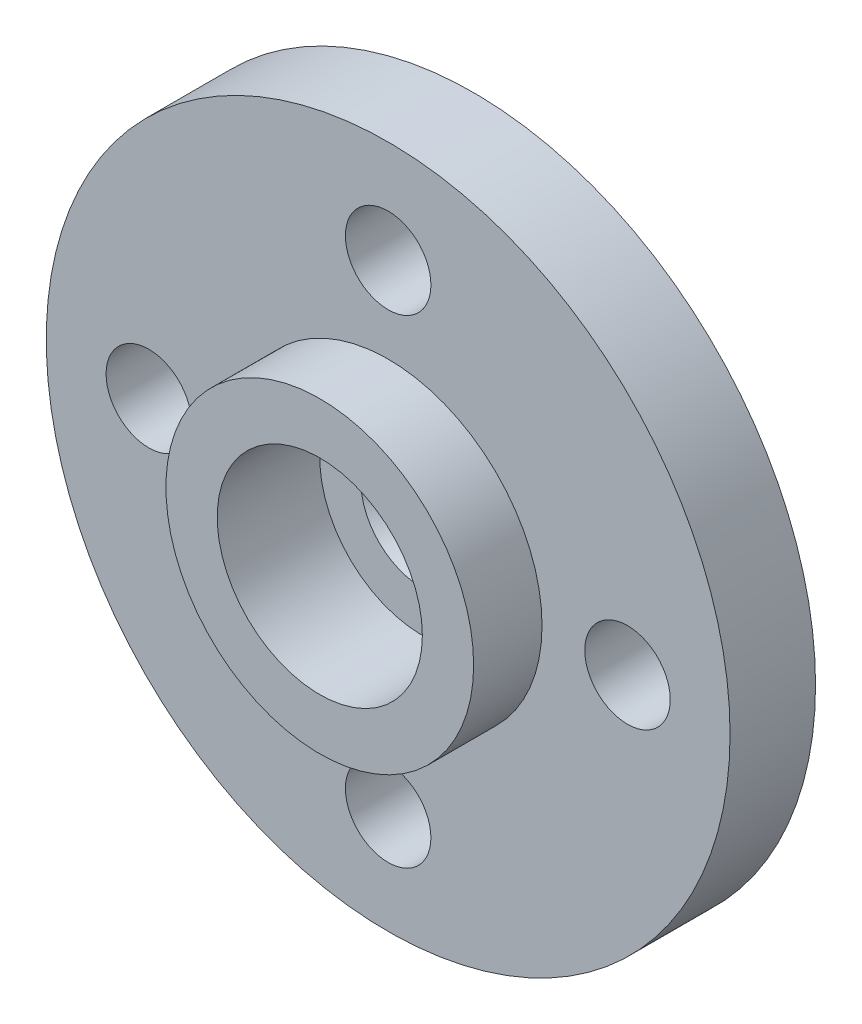
SolidWorks part; units mm, degrees
ref_plane "前视基准面" through (0, 0, 0) normal (0, 0, 1) x (1, 0, 0)
ref_plane "上视基准面" through (0, 0, 0) normal (0, 1, 0) x (1, 0, 0)
ref_plane "右视基准面" through (0, 0, 0) normal (1, 0, 0) x (0, 0, -1)
other "Configuration Table"
sketch "草图1" plane through (0, 0, 0) normal (0, 0, 1) x (1, 0, 0)
  circle A0 centre (0, 0) radius 10
  circle A1 centre (0, 0) radius 7 construction
  circle A2 centre (0, 7) radius 0.5
  circle A3 centre (7, 0) radius 0.5
  circle A4 centre (0, -7) radius 0.5
  circle A5 centre (-7, 0) radius 0.5
  circle A6 centre (0, 0) radius 1.5
  dimension "D1" = 1
  dimension "D2" = 1
  dimension "D3" = 1
  dimension "D4" = 1
  dimension "D5" = 20
  dimension "D6" = 14
  dimension "D7" = 3
extrude "凸台-拉伸1" add sketch "草图1" along normal blind 2.5
sketch "草图2" plane through (0, 0, 2.5) normal (0, 0, 1) x (1, 0, 0)
  circle A0 centre (0, 0) radius 4.5
  circle A1 centre (0, 0) radius 3
  dimension "D1" = 9
  dimension "D2" = 6
extrude "凸台-拉伸2" add sketch "草图2" along normal blind 2
sketch "草图3" plane through (0, 0, 2.5) normal (0, 0, 1) x (1, 0, 0)
  circle A0 centre (0, 0) radius 3
extrude "切除-拉伸1" cut sketch "草图3" against normal blind 1
chamfer "倒角1" distance 0.3 angle 45 1 edges at (1.5, 0, 1.5)
hole_wizard "M3 螺纹孔的螺纹孔钻头1" positions "草图4" profile "草图5" hole size "M3" standard "GB"
sketch "草图4" plane through (0, 0, 0) normal (0, 0, -1) x (-1, 0, 0)
  point P0 (0, 7)
  point P3 (7, 0)
  point P6 (0, -7)
  point P9 (-7, 0)
sketch "草图5" plane through (0, 7, 0) normal (1, 0, 0) x (0, 1, 0)
  line L0 (0, 0) -> (0, 7.2511)
  line L1 (0, 7.2511) -> (1.25, 6.5)
  line L2 (1.25, 6.5) -> (1.25, 0)
  line L5 (1.25, 0) -> (0, 0)
  line L10 (0, 7.2511) -> (-1.25, 6.5) construction
  line L11 (0, -6.35) -> (0, 107.95) construction
  dimension "孔直径" = 2.5
  dimension "孔深度" = 6.5
  dimension "导头角度" = 118
cosmetic thread "装饰螺纹线1" parameters "D2"=3
cosmetic thread "装饰螺纹线2" parameters "D2"=3
cosmetic thread "装饰螺纹线3" parameters "D2"=3
cosmetic thread "装饰螺纹线4" parameters "D2"=3
